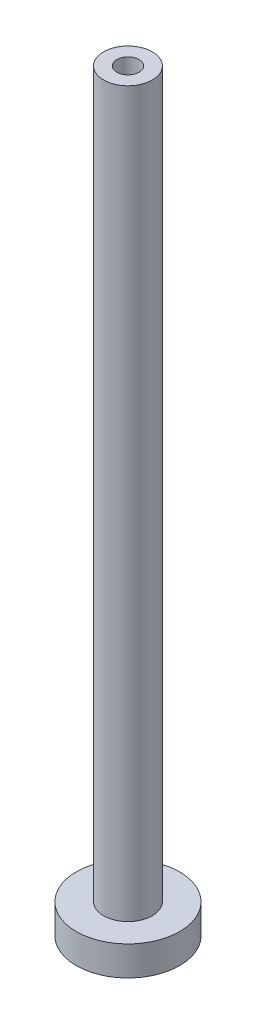
SolidWorks part; units mm, degrees
ref_plane "Front Plane" through (0, 0, 0) normal (0, 0, 1) x (1, 0, 0)
ref_plane "Top Plane" through (0, 0, 0) normal (0, 1, 0) x (1, 0, 0)
ref_plane "Right Plane" through (0, 0, 0) normal (1, 0, 0) x (0, 0, -1)
sketch "Sketch1" plane through (0, 0, 0) normal (0, 1, 0) x (1, 0, 0)
  circle A0 centre (0, 0) radius 7
  dimension "D1" = 14
extrude "Boss-Extrude1" add sketch "Sketch1" along normal blind 4
sketch "Sketch2" plane through (0, 4, 0) normal (0, 1, 0) x (1, 0, 0)
  circle A0 centre (0, 0) radius 3.3
  dimension "D1" = 6.6
extrude "Boss-Extrude2" add sketch "Sketch2" along normal blind 86
sketch "Sketch3" plane through (0, 90, 0) normal (0, 1, 0) x (1, 0, 0)
  circle A0 centre (0, 0) radius 3.3 construction
  circle A1 centre (0, 0) radius 3.3
extrude "Boss-Extrude3" add sketch "Sketch3" along normal blind 12
sketch "Sketch4" plane through (0, 102, 0) normal (0, 1, 0) x (1, 0, 0)
  circle A0 centre (0, 0) radius 1.5
  dimension "D1" = 3
extrude "Cut-Extrude2" cut sketch "Sketch4" against normal through all contours A0
